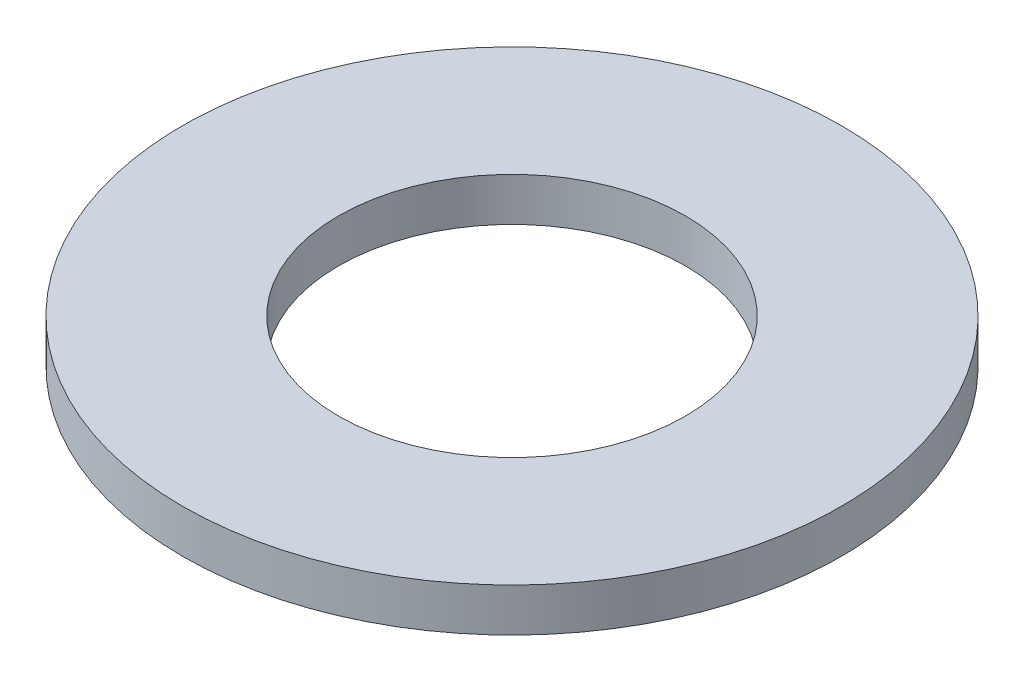
SolidWorks part; units mm, degrees
material "Balsa"
ref_plane "Front Plane" through (0, 0, 0) normal (0, 0, 1) x (1, 0, 0)
ref_plane "Top Plane" through (0, 0, 0) normal (0, 1, 0) x (1, 0, 0)
ref_plane "Right Plane" through (0, 0, 0) normal (1, 0, 0) x (0, 0, -1)
sketch "Sketch1" plane through (0, 0, 0) normal (0, 1, 0) x (1, 0, 0)
  circle A0 centre (0, 0) radius 38
  circle A1 centre (0, 0) radius 20
  dimension "D1" = 76
  dimension "D2" = 40
extrude "Boss-Extrude1" add sketch "Sketch1" along normal blind 5
